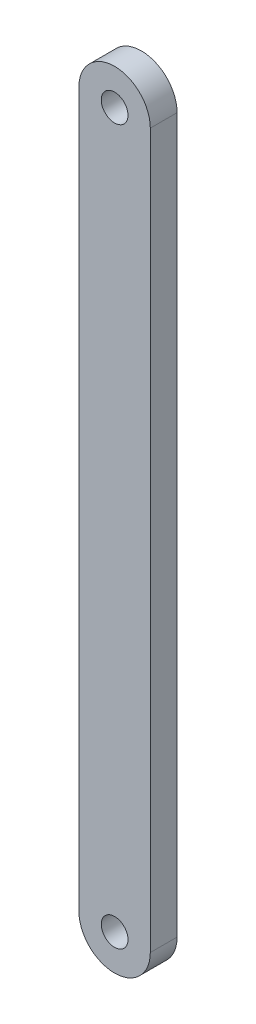
SolidWorks part; units mm, degrees
ref_plane "前基準面" through (0, 0, 0) normal (0, 0, 1) x (1, 0, 0)
ref_plane "上基準面" through (0, 0, 0) normal (0, 1, 0) x (1, 0, 0)
ref_plane "右基準面" through (0, 0, 0) normal (1, 0, 0) x (0, 0, -1)
sketch "草圖1" plane through (0, 0, 0) normal (0, 0, 1) x (1, 0, 0)
  line L0 (32.3001, 85.0001) -> (32.3001, 5)
  line L1 (40.3001, 5) -> (40.3001, 85)
  arc A0 (32.3001, 85.0001) -> (40.3001, 85) centre (36.3001, 85) cw
  arc A1 (40.3001, 85) -> (32.3001, 85) centre (36.3001, 85) ccw construction
  circle A2 centre (36.3001, 85) radius 1.5
  circle A3 centre (36.3001, 85) radius 1.5 construction
  circle A5 centre (36.3001, 5) radius 1.5 construction
  circle A6 centre (36.3001, 5) radius 1.5
  spline S2 degree 3 poles (40.3001, 5) (40.3001, 2.6568) (38.6432, 1) (36.3001, 1) (33.9569, 1) (32.3, 2.6569) (32.3001, 5.0001) knots 0 0 0 0 0.5 0.5 0.5 1 1 1 1 weights 1 0.804735 0.804735 1 0.804735 0.804735 1 construction
  spline S3 degree 3 poles (40.3001, 5) (40.3001, 2.6568) (38.6432, 1) (36.3001, 1) (33.9569, 1) (32.3, 2.6569) (32.3001, 5.0001) knots 0 0 0 0 0.5 0.5 0.5 1 1 1 1 weights 1 0.804735 0.804735 1 0.804735 0.804735 1
extrude "填料-伸長1" add sketch "草圖1" along normal blind 3 contours S3 L1 A0 L0 A6 A2
